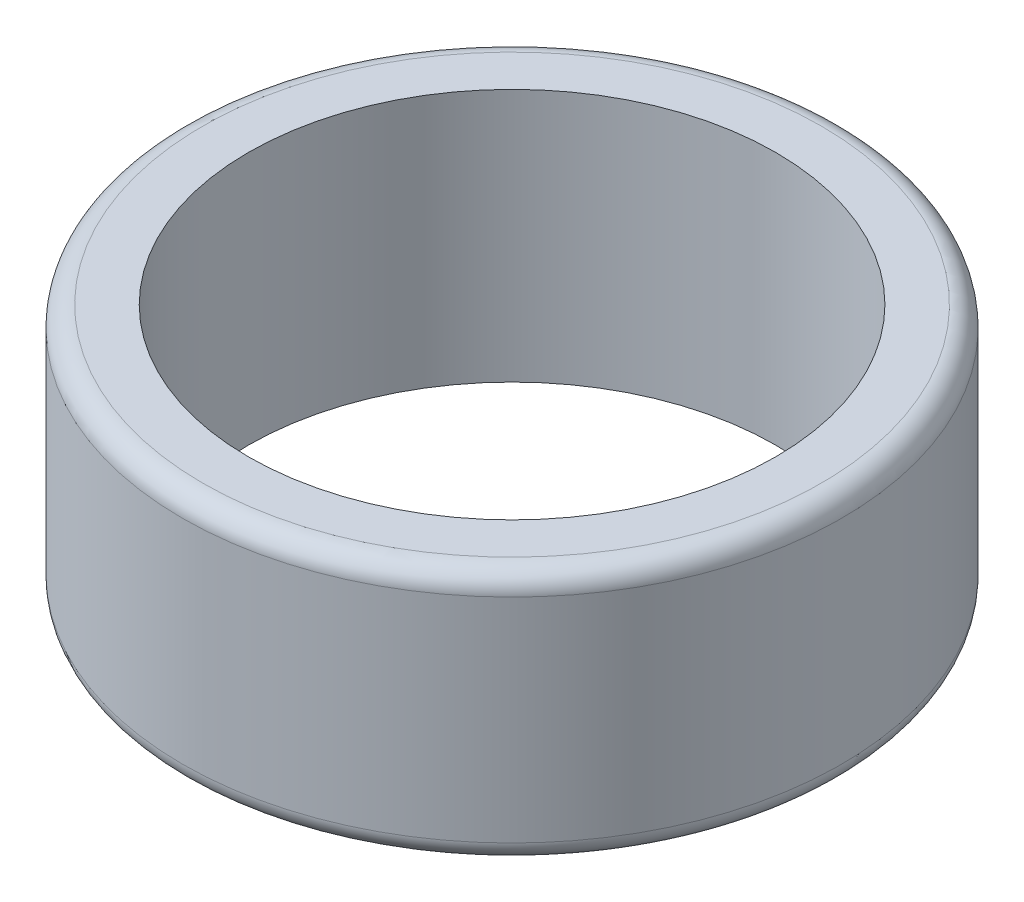
SolidWorks part; units mm, degrees
ref_plane "Front Plane" through (0, 0, 0) normal (0, 0, 1) x (1, 0, 0)
ref_plane "Top Plane" through (0, 0, 0) normal (0, 1, 0) x (1, 0, 0)
ref_plane "Right Plane" through (0, 0, 0) normal (1, 0, 0) x (0, 0, -1)
sketch "Sketch2" plane through (0, 0, 0) normal (0, 1, 0) x (1, 0, 0)
  circle A0 centre (0, 0) radius 26
  circle A1 centre (0, 0) radius 32.5
  dimension "D1" = 52
  dimension "D2" = 65
extrude "Boss-Extrude1" add sketch "Sketch2" along normal blind 25
fillet "Fillet2" radius 2 2 edges at (0, 25, 32.5) (0, 0, 32.5)
